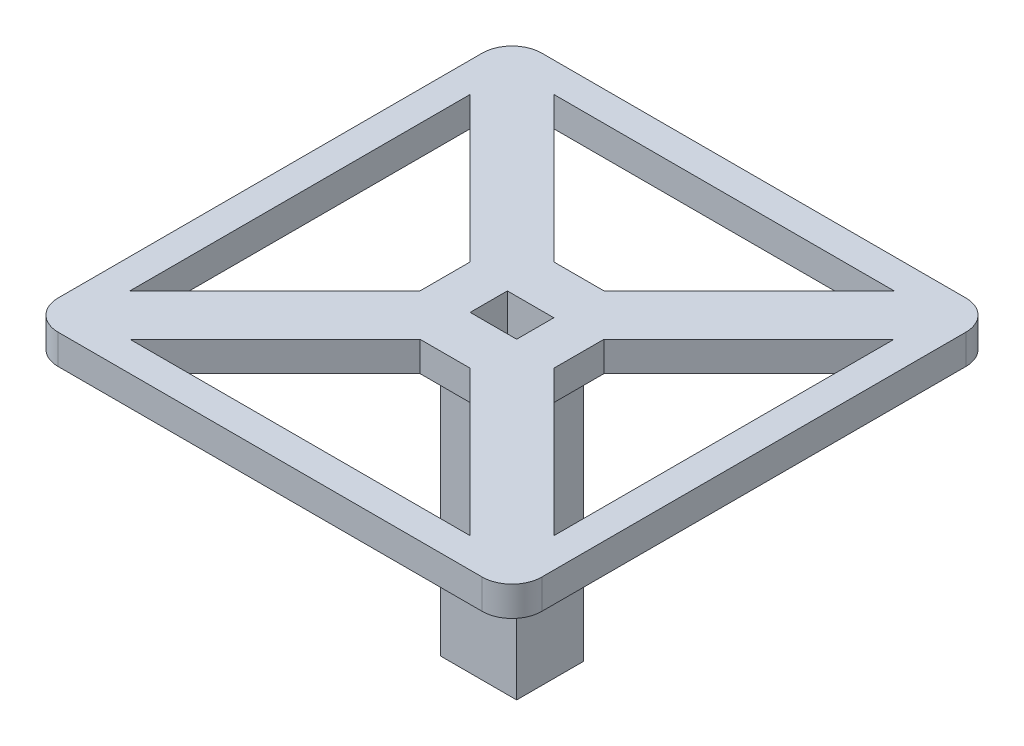
SolidWorks part; units mm, degrees
ref_plane "Front Plane" through (0, 0, 0) normal (0, 0, 1) x (1, 0, 0)
ref_plane "Top Plane" through (0, 0, 0) normal (0, 1, 0) x (1, 0, 0)
ref_plane "Right Plane" through (0, 0, 0) normal (1, 0, 0) x (0, 0, -1)
sketch "Sketch1" plane through (0, 0, 0) normal (0, 1, 0) x (1, 0, 0)
  line L1 (-1.9844, -1.5875) -> (1.9844, -1.5875)
  line L2 (-1.9844, -1.5875) -> (-1.9844, 1.5875)
  line L3 (-1.9844, 1.5875) -> (1.9844, 1.5875)
  line L4 (1.9844, -1.5875) -> (1.9844, 1.5875)
  line L5 (-1.9844, -1.5875) -> (1.9844, 1.5875) construction
  line L6 (-1.9844, 1.5875) -> (1.9844, -1.5875) construction
  line L7 (-3.2544, -2.8575) -> (3.2544, -2.8575)
  line L8 (-3.2544, -2.8575) -> (-3.2544, 2.8575)
  line L9 (-3.2544, 2.8575) -> (3.2544, 2.8575)
  line L10 (3.2544, -2.8575) -> (3.2544, 2.8575)
  line L11 (-3.2544, -2.8575) -> (3.2544, 2.8575) construction
  line L12 (-3.2544, 2.8575) -> (3.2544, -2.8575) construction
  point P0 (0, 0)
  point P6 (0, 0)
  dimension "D1" = 3.9688
  dimension "D2" = 3.175
  dimension "D3" = 1.27
  dimension "D4" = 1.27
extrude "Boss-Extrude1" add sketch "Sketch1" along normal blind 25.4
sketch "Sketch2" plane through (0, 25.4, 0) normal (0, 1, 0) x (1, 0, 0)
  line L0 (-3.2544, -2.8575) -> (3.2544, -2.8575) construction
  line L1 (3.2544, -2.8575) -> (3.2544, 2.8575) construction
  line L2 (3.2544, 2.8575) -> (-3.2544, 2.8575) construction
  line L3 (-3.2544, 2.8575) -> (-3.2544, -2.8575) construction
  line L4 (-3.2544, -2.8575) -> (3.2544, -2.8575)
  line L5 (3.2544, -2.8575) -> (3.2544, 2.8575)
  line L6 (3.2544, 2.8575) -> (-3.2544, 2.8575)
  line L7 (-3.2544, 2.8575) -> (-3.2544, -2.8575)
  line L9 (-20.6375, -20.6375) -> (20.6375, -20.6375)
  line L10 (-20.6375, -20.6375) -> (-20.6375, 20.6375)
  line L11 (-20.6375, 20.6375) -> (20.6375, 20.6375)
  line L12 (20.6375, -20.6375) -> (20.6375, 20.6375)
  line L13 (-20.6375, -20.6375) -> (20.6375, 20.6375) construction
  line L14 (-20.6375, 20.6375) -> (20.6375, -20.6375) construction
  point P2 (0, 0)
  dimension "D1" = 41.275
extrude "Boss-Extrude2" add sketch "Sketch2" against normal blind 2.54
sketch "Sketch3" plane through (0, 25.4, 0) normal (0, 1, 0) x (1, 0, 0)
  line L0 (-3.175, 3.175) -> (-20.6375, 20.6375) construction
  line L1 (-3.175, -3.175) -> (3.175, -3.175) construction
  line L2 (-3.175, -3.175) -> (-3.175, 3.175) construction
  line L3 (-3.175, 3.175) -> (3.175, 3.175) construction
  line L4 (3.175, -3.175) -> (3.175, 3.175) construction
  line L5 (-20.6375, 20.6375) -> (20.6375, 20.6375) construction
  line L6 (20.6375, 20.6375) -> (3.175, 3.175) construction
  line L7 (20.6375, 20.6375) -> (20.6375, -20.6375) construction
  line L8 (20.6375, -20.6375) -> (3.175, -3.175) construction
  line L9 (-20.6375, 20.6375) -> (-20.6375, -20.6375) construction
  line L10 (-20.6375, -20.6375) -> (-3.175, -3.175) construction
  line L11 (-20.6375, -20.6375) -> (20.6375, -20.6375) construction
  line L12 (-2.1229, 5.715) -> (-14.5054, 18.0975)
  line L13 (-14.5054, 18.0975) -> (14.5054, 18.0975)
  line L14 (14.5054, 18.0975) -> (2.1229, 5.715)
  line L15 (-2.1229, 5.715) -> (2.1229, 5.715)
  line L16 (-5.715, 2.1229) -> (-18.0975, 14.5054)
  line L17 (-18.0975, 14.5054) -> (-18.0975, -14.5054)
  line L18 (-18.0975, -14.5054) -> (-5.715, -2.1229)
  line L19 (-5.715, -2.1229) -> (-5.715, 2.1229)
  line L20 (-14.5054, -18.0975) -> (-2.1229, -5.715)
  line L21 (-2.1229, -5.715) -> (2.1229, -5.715)
  line L22 (14.5054, -18.0975) -> (2.1229, -5.715)
  line L23 (-14.5054, -18.0975) -> (14.5054, -18.0975)
  line L24 (18.0975, 14.5054) -> (5.715, 2.1229)
  line L25 (5.715, -2.1229) -> (5.715, 2.1229)
  line L26 (18.0975, -14.5054) -> (5.715, -2.1229)
  line L27 (18.0975, 14.5054) -> (18.0975, -14.5054)
  point P0 (0, 0)
  point P10 (0, 0)
  point P15 (-5.0804, 5.2496)
  point P16 (0, 3.175)
  dimension "D1" = 6.35
  dimension "D2" = 2.54
  dimension "D3" = 2.54
  dimension "D4" = 2.54
  dimension "D5" = 2.54
extrude "Cut-Extrude1" cut sketch "Sketch3" against normal through all
fillet "Fillet1" radius 2.54 4 edges at (20.6375, 24.13, -20.6375) (20.6375, 24.13, 20.6375) (-20.6375, 24.13, 20.6375) (-20.6375, 24.13, -20.6375)
